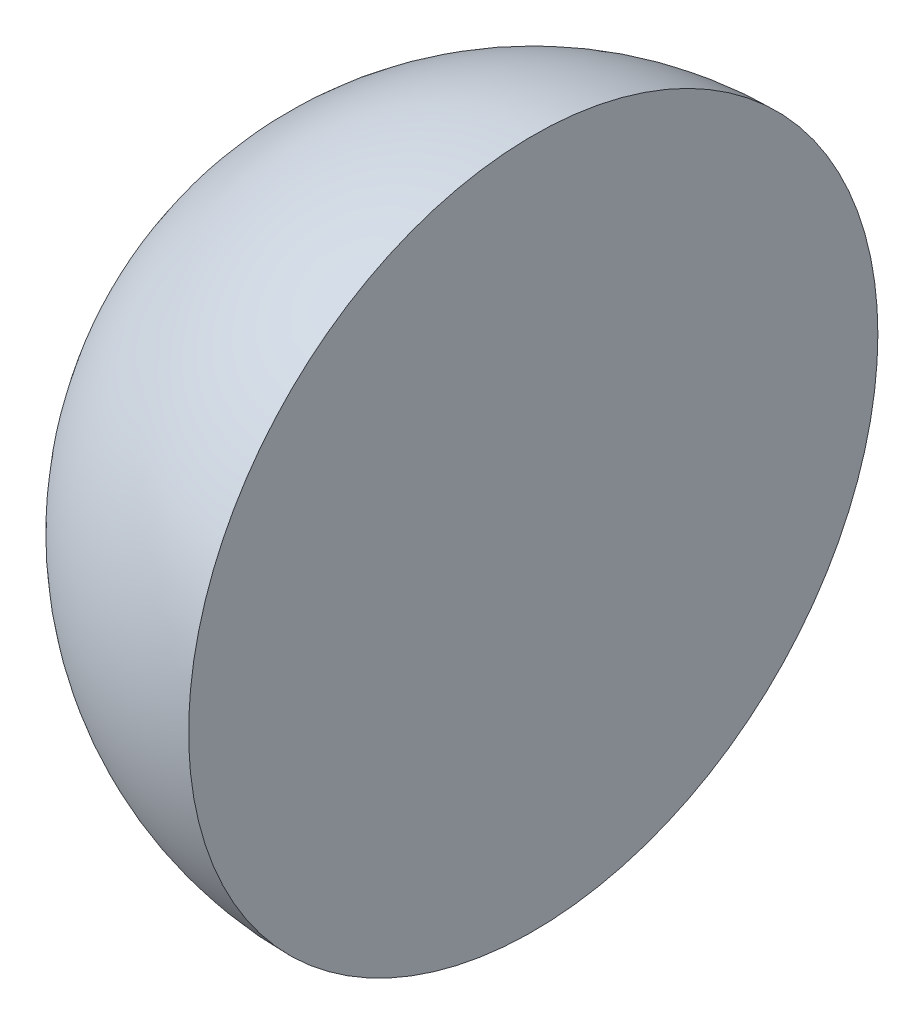
SolidWorks part; units mm, degrees
material "Polyurethane Foam Flexible"
ref_plane "Front Plane" through (0, 0, 0) normal (0, 0, 1) x (1, 0, 0)
ref_plane "Top Plane" through (0, 0, 0) normal (0, 1, 0) x (1, 0, 0)
ref_plane "Right Plane" through (0, 0, 0) normal (1, 0, 0) x (0, 0, -1)
sketch "Sketch1" plane through (0, 0, 0) normal (0, 0, 1) x (1, 0, 0)
  line L0 (0, 153.1806) -> (0, -37.3194) construction
  line L1 (0, 153.1806) -> (0, -37.3194)
  arc A0 (0, 153.1806) -> (0, -37.3194) centre (0, 57.9306) cw
revolve "Revolve1" add sketch "Sketch1" angle 360 about L0
sketch "Sketch2" plane through (0, 0, 0) normal (1, 0, 0) x (0, 0, -1)
  line L1 (-147.6601, 164.0257) -> (147.6601, 164.0257)
  line L2 (-147.6601, 164.0257) -> (-147.6601, -164.0257)
  line L3 (-147.6601, -164.0257) -> (147.6601, -164.0257)
  line L4 (147.6601, 164.0257) -> (147.6601, -164.0257)
  line L5 (-147.6601, 164.0257) -> (147.6601, -164.0257) construction
  line L6 (-147.6601, -164.0257) -> (147.6601, 164.0257) construction
  point P0 (0, 0)
extrude "Cut-Extrude1" cut sketch "Sketch2" along normal blind 95.25
ref_plane "Plane1" through (-95.25, 0, 0) normal (-1, 0, 0) x (0, 0, 1)
